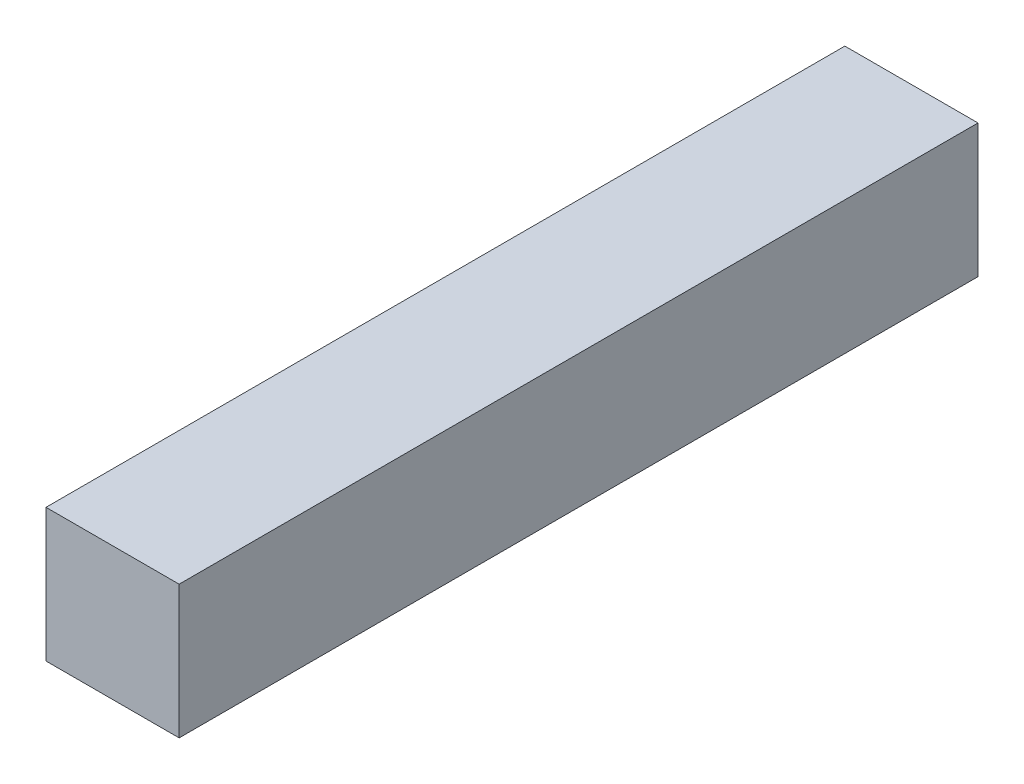
SolidWorks part; units mm, degrees
ref_plane "Front Plane" through (0, 0, 0) normal (0, 0, 1) x (1, 0, 0)
ref_plane "Top Plane" through (0, 0, 0) normal (0, 1, 0) x (1, 0, 0)
ref_plane "Right Plane" through (0, 0, 0) normal (1, 0, 0) x (0, 0, -1)
sketch "Sketch2" plane through (0, 0, 0) normal (0, 0, 1) x (1, 0, 0)
  line L1 (-12.5, 12.5) -> (12.5, 12.5)
  line L2 (-12.5, 12.5) -> (-12.5, -12.5)
  line L3 (-12.5, -12.5) -> (12.5, -12.5)
  line L4 (12.5, 12.5) -> (12.5, -12.5)
  line L5 (-12.5, 12.5) -> (12.5, -12.5) construction
  line L6 (-12.5, -12.5) -> (12.5, 12.5) construction
  point P0 (0, 0)
  dimension "D1" = 25
  dimension "D2" = 25
extrude "Boss-Extrude1" add sketch "Sketch2" along normal mid plane 150
